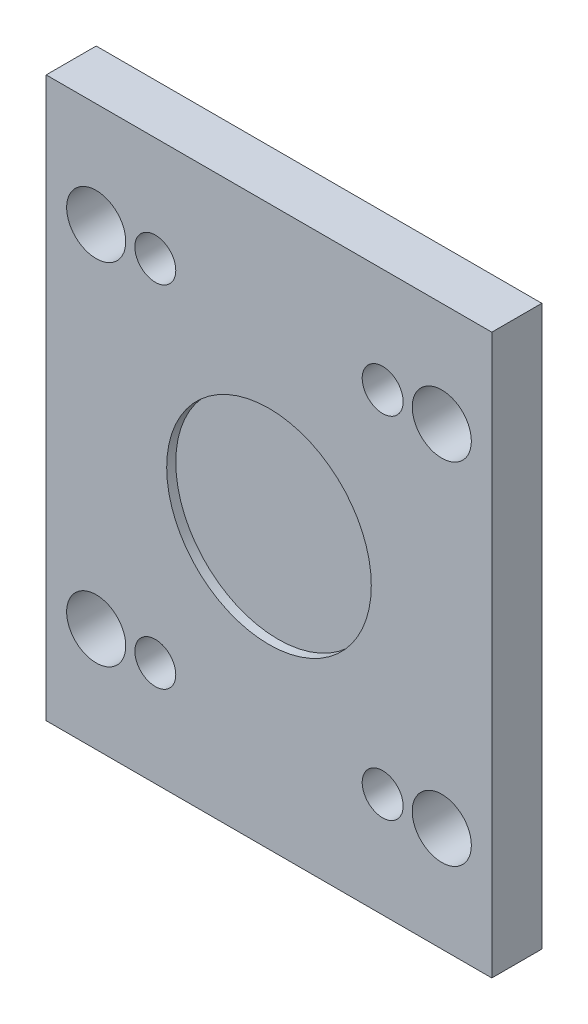
SolidWorks part; units mm, degrees
ref_plane "Спереди" through (0, 0, 0) normal (0, 0, 1) x (1, 0, 0)
ref_plane "Сверху" through (0, 0, 0) normal (0, 1, 0) x (1, 0, 0)
ref_plane "Справа" through (0, 0, 0) normal (1, 0, 0) x (0, 0, -1)
ref_plane "Плоскость4" through (0, 0, 22) normal (0, 0, 1) x (1, 0, 0)
sketch "Эскиз1" plane through (0, 0, 22) normal (0, 0, 1) x (1, 0, 0)
  line L0 (98, 123) -> (-98, 123)
  line L1 (-98, 123) -> (-98, -123)
  line L2 (-98, -123) -> (98, -123)
  line L3 (98, -123) -> (98, 123)
extrude "Бобышка-Вытянуть1" add sketch "Эскиз1" against normal blind 22
hole_wizard "Цековка для  болта с шестигранной головкой M101" positions "Эскиз3" profile "Эскиз2" counterbore size "M10" standard "Ansi Metric"
sketch "Эскиз3" plane through (0, 0, 22) normal (0, 0, 1) x (1, 0, 0)
  point P0 (50, 77)
  point P1 (50, -77)
  point P2 (-50, 77)
  point P3 (-50, -77)
sketch "Эскиз2" plane through (50, 77, 22) normal (1, 0, 0) x (0, -1, 0)
  line L0 (0, 0) -> (0, 22)
  line L1 (0, 22) -> (5.5, 22)
  line L3 (5.5, 22) -> (5.5, 13)
  line L4 (5.5, 13) -> (9, 13)
  line L5 (9, 13) -> (9, 0)
  line L7 (9, 0) -> (0, 0)
  line L11 (0, -6.35) -> (0, 107.95) construction
  dimension "Диаметр сквозного отверстия" = 11
  dimension "Глубина сквозного отверстия" = 22
  dimension "Диаметр цековки" = 18
  dimension "Глубина цековки" = 13
hole_wizard "Отверстие с зазором M221" positions "Эскиз5" profile "Эскиз4" hole size "M22" standard "Ansi Metric"
sketch "Эскиз5" plane through (0, 0, 22) normal (0, 0, 1) x (1, 0, 0)
  point P0 (76, 77)
  point P1 (76, -77)
  point P2 (-76, -77)
  point P3 (-76, 77)
sketch "Эскиз4" plane through (76, 77, 22) normal (1, 0, 0) x (0, -1, 0)
  line L0 (0, 0) -> (0, 22)
  line L1 (0, 22) -> (13, 22)
  line L2 (13, 22) -> (13, 0)
  line L5 (13, 0) -> (0, 0)
  line L11 (0, -6.35) -> (0, 107.95) construction
  dimension "Диаметр сквозного отверстия" = 26
  dimension "Глубина сквозного отверстия" = 22
hole_wizard "Отверстие с зазором M801" positions "Эскиз7" profile "Эскиз6" hole size "M80" standard "Ansi Metric"
sketch "Эскиз7" plane through (0, 0, 22) normal (0, 0, 1) x (1, 0, 0)
  point P0 (0, 0)
sketch "Эскиз6" plane through (0, 0, 22) normal (1, 0, 0) x (0, -1, 0)
  line L0 (0, 0) -> (0, 4)
  line L1 (0, 4) -> (45, 4)
  line L2 (45, 4) -> (45, 0)
  line L5 (45, 0) -> (0, 0)
  line L10 (0, 4) -> (-45, 4) construction
  line L11 (0, -6.35) -> (0, 107.95) construction
  dimension "Диаметр отверстия" = 90
  dimension "Глубина отверстия" = 4
  dimension "Угол заточки сверла" = 180
